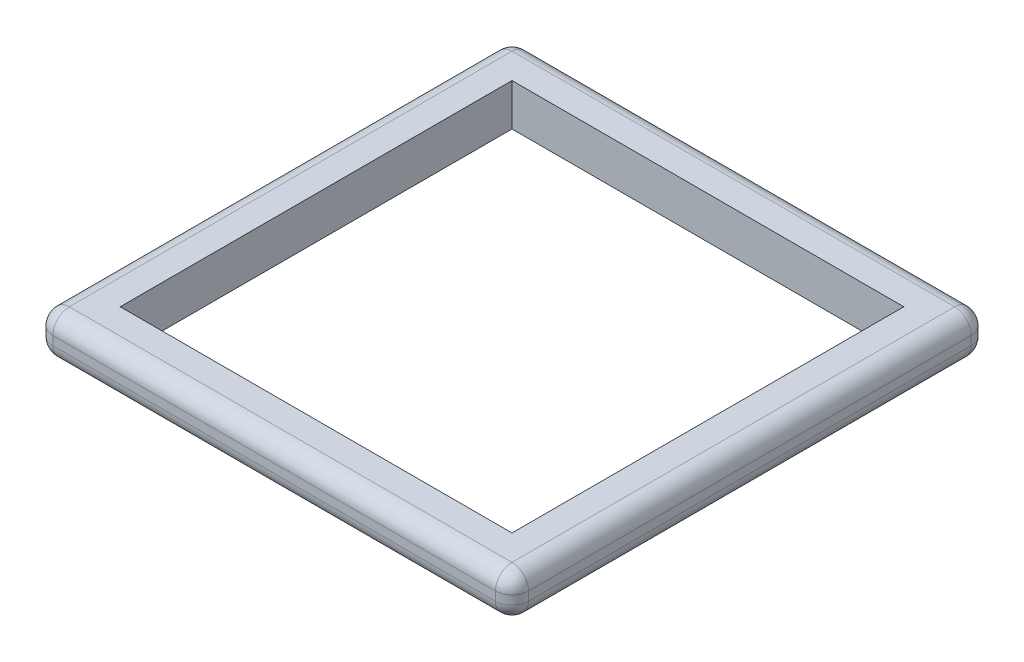
SolidWorks part; units mm, degrees
ref_plane "Front Plane" through (0, 0, 0) normal (0, 0, 1) x (1, 0, 0)
ref_plane "Top Plane" through (0, 0, 0) normal (0, 1, 0) x (1, 0, 0)
ref_plane "Right Plane" through (0, 0, 0) normal (1, 0, 0) x (0, 0, -1)
sketch "Sketch1" plane through (0, 0, 0) normal (0, 1, 0) x (1, 0, 0)
  line L1 (0, 0) -> (-711.2, 0)
  line L2 (0, 0) -> (0, -711.2)
  line L3 (0, -711.2) -> (-711.2, -711.2)
  line L4 (-711.2, 0) -> (-711.2, -711.2)
  dimension "D1" = 711.2
  dimension "D2" = 711.2
extrude "Extrude-Thin1" add sketch "Sketch1" along normal blind 76.2 thin
fillet "Fillet1" radius 30 12 edges at (-355.6, 76.2, 787.4) (-787.4, 76.2, 355.6) (-355.6, 76.2, -76.2) (76.2, 76.2, 355.6) (-787.4, 38.1, -76.2) (-787.4, 38.1, 787.4) (76.2, 38.1, -76.2) (76.2, 38.1, 787.4) (-787.4, 0, 355.6) (-355.6, 0, -76.2) (-355.6, 0, 787.4) (76.2, 0, 355.6)
